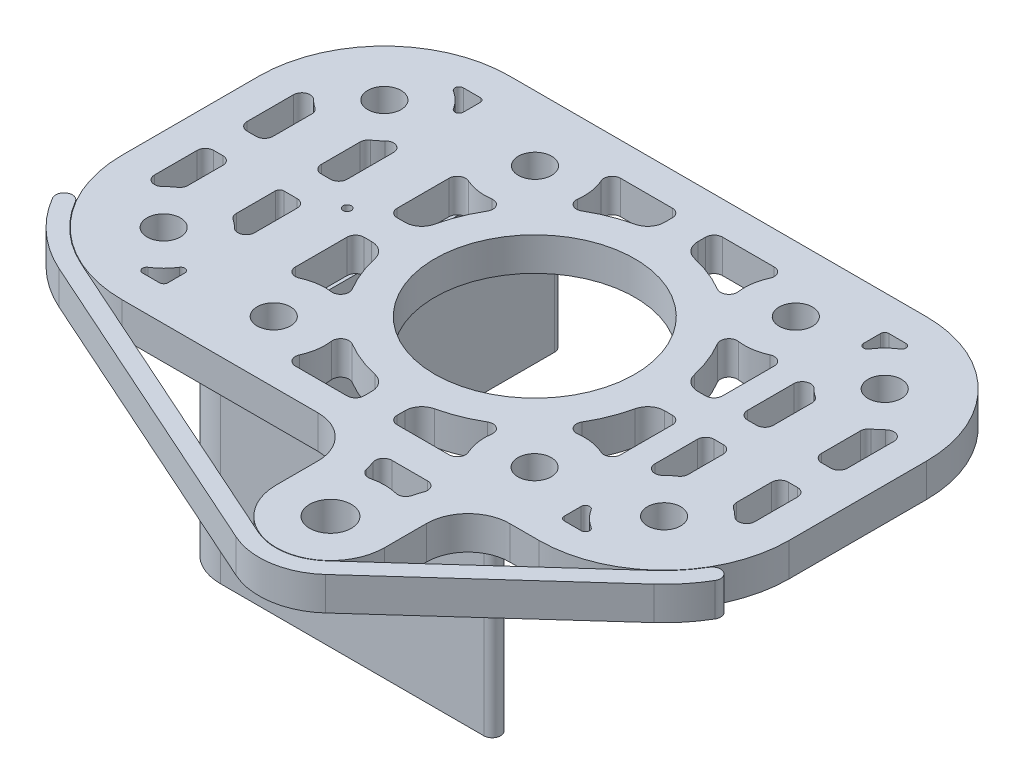
SolidWorks part; units mm, degrees
ref_plane "Front Plane" through (0, 0, 0) normal (0, 0, 1) x (1, 0, 0)
ref_plane "Top Plane" through (0, 0, 0) normal (0, 1, 0) x (1, 0, 0)
ref_plane "Right Plane" through (0, 0, 0) normal (1, 0, 0) x (0, 0, -1)
sketch "Sketch1" plane through (0, 0, 0) normal (0, 1, 0) x (1, 0, 0)
  line L1 (-21.5, 13.9196) -> (-21.5, 17.5) construction
  line L2 (-17.5, -21.5) -> (17.5, -21.5) construction
  line L3 (19.5, -3) -> (19.5, -9.2063)
  line L4 (19.5, 9.2063) -> (19.5, 3)
  line L5 (21.5, 21.5) -> (-21.5, -21.5) construction
  line L7 (-17.5, 21.5) -> (17.5, 21.5) construction
  line L8 (-11.4637, 10) -> (-11.4637, -10) construction
  line L9 (-11.4637, 10) -> (-11.4637, -10) construction
  line L10 (0, 0) -> (0, 15.6621) construction
  line L11 (0, 15.6621) -> (-15.6378, 15.6621) construction
  line L13 (-26.5, -23) -> (-3, -23)
  line L14 (0, -21.5) -> (0, 38.5) construction
  line L15 (-26.5, 23.4637) -> (23.5, 23.4637)
  line L16 (38.5, -8) -> (38.5, 8.4637)
  line L17 (21.5, -17.5) -> (21.5, 17.5) construction
  line L18 (-41.5, 8.4637) -> (-41.5, -8)
  line L19 (-31.5, 7.4637) -> (-31.5, -7) construction
  line L21 (-21.5, -21.5) -> (21.5, 21.5) construction
  line L22 (18.5, 2) -> (17.5499, 2)
  line L23 (-34.4, 7.6508) -> (-34.4, 3)
  line L27 (-28.6, 7.6508) -> (-28.6, 3)
  line L28 (-25.5, 8.5647) -> (-25.5, 3)
  line L29 (-37.5, -8.101) -> (-37.5, -3)
  line L30 (18.5, -2) -> (17.5499, -2)
  line L31 (-3, -19.5) -> (-9.2063, -19.5)
  line L32 (9.2063, -19.5) -> (3, -19.5)
  line L33 (12.6, -23) -> (12.6, -43) construction
  line L34 (2, -18.5) -> (2, -17.5499)
  line L35 (-2, -18.5) -> (-2, -17.5499)
  line L36 (-19.5, 3) -> (-19.5, 9.2063)
  line L37 (-19.5, -9.2063) -> (-19.5, -3)
  line L38 (-18.5, -2) -> (-17.5499, -2)
  line L39 (-9.2063, 19.5) -> (-3, 19.5)
  line L40 (-25.5, 16.9278) -> (-25.5, 18.9637)
  line L41 (2, 18.5) -> (2, 17.5499)
  line L42 (-2, 18.5) -> (-2, 17.5499)
  line L43 (3, 19.5) -> (9.2063, 19.5)
  line L44 (0, 23.4637) -> (0, 16) construction
  line L45 (-18.5, 2) -> (-17.5499, 2)
  line L47 (18.5, 38.5) -> (38.5, 38.5) construction
  line L48 (-26.5, -2) -> (-28.1, -2)
  line L51 (-25.5, -16.4641) -> (-25.5, -18.5)
  line L52 (-20.3267, -20.3302) -> (-20.3284, -20.3284)
  line L53 (-28.0359, -19) -> (-26, -19)
  line L54 (0, -23.4637) -> (0, -16) construction
  line L55 (-21.5, 623) -> (-21.5, -43) construction
  line L56 (18.5, -23) -> (18.5, 603) construction
  line L57 (12.8901, -37.861) -> (33.5871, -19.1693)
  line L58 (-19.5, -23) -> (-15.6, -23) construction
  line L59 (5.8213, -38.9772) -> (-32.6549, -21.7339)
  line L60 (12.6, -43) -> (12.6, -63) construction
  line L61 (-18.9133, -18.9151) -> (-18.9142, -18.9142)
  line L62 (-26.5, 2) -> (-27.6, 2)
  line L63 (-21.5, 38.5) -> (-41.5, 38.5) construction
  line L65 (-28.0359, 19.4637) -> (-26, 19.4637)
  line L66 (23, -19.4637) -> (25.0359, -19.4637)
  line L67 (-34.4, -3) -> (-34.4, -7.1871)
  line L68 (-37.5, 3) -> (-37.5, 8.5647)
  line L69 (-35.4, 2) -> (-36.5, 2)
  line L70 (-35.4, -2) -> (-36.5, -2)
  line L71 (-28.6, -2.5) -> (-28.6, -7.1871)
  line L72 (-25.5, -3) -> (-25.5, -8.101)
  line L73 (22.5, -8.101) -> (22.5, -3)
  line L74 (28.5, 7.4637) -> (28.5, -7) construction
  line L75 (-26.5, -3) -> (-18.5, 3) construction
  line L76 (-31.5, 27.4637) -> (28.5, 27.4637) construction
  line L77 (-26.5, 3) -> (-18.5, -3) construction
  line L78 (22.5, 16.9278) -> (22.5, 18.9637)
  line L79 (34.5, -8.101) -> (34.5, -3)
  line L80 (25.6, 7.6508) -> (25.6, 3)
  line L81 (31.4, 7.6508) -> (31.4, 3)
  line L82 (23, 19.4637) -> (25.0359, 19.4637)
  line L83 (22.5, -16.9278) -> (22.5, -18.9637)
  line L84 (17.5499, 2) -> (17.5499, -2) construction
  line L85 (22.5, 0) -> (25.6, 0) construction
  line L86 (23.5, -2) -> (24.6, -2)
  line L87 (23.5, 2) -> (24.6, 2)
  line L88 (-31.5, 23.4637) -> (28.5, 23.4637) construction
  line L89 (15, -33) -> (15, -28)
  line L90 (32.4, -2) -> (33.5, -2)
  line L91 (25.6, -3) -> (25.6, -7.1871)
  line L92 (28.5, 38.5) -> (28.5, 26.8752) construction
  line L93 (31.4, -3) -> (31.4, -7.1871)
  line L94 (32.4, 2) -> (33.5, 2)
  line L95 (22.5, 3) -> (22.5, 8.5647)
  line L96 (34.5, 3) -> (34.5, 8.5647)
  line L97 (2, -33) -> (2, -28)
  line L98 (20, -23) -> (23.5, -23)
  line L100 (5.0034, -40.8023) -> (-33.4728, -23.559)
  line L101 (10.6325, -23.5) -> (6.3675, -23.5)
  line L102 (14.2306, -39.3453) -> (34.9276, -20.6536)
  line L103 (9.2063, -23.5) -> (3, -23.5) construction
  arc A0 (23.5, -23) -> (38.5, -8) centre (23.5, -8) ccw
  arc A1 (38.5, 8.4637) -> (23.5, 23.4637) centre (23.5, 8.4637) ccw
  arc A2 (-26.5, 23.4637) -> (-41.5, 8.4637) centre (-26.5, 8.4637) ccw
  arc A3 (-17.5, 21.5) -> (-21.5, 17.5) centre (-17.5, 17.5) ccw construction
  arc A4 (-21.5, -17.5) -> (-17.5, -21.5) centre (-17.5, -17.5) ccw construction
  arc A5 (-41.5, -8) -> (-26.5, -23) centre (-26.5, -8) ccw
  circle A7 centre (-31.5, 13.4637) radius 2
  circle A9 centre (28.5, 13.4637) radius 2
  circle A10 centre (0, 0) radius 12
  circle A11 centre (-15.6378, 15.6621) radius 2
  circle A12 centre (15.6621, 15.6378) radius 2
  circle A13 centre (0, 0) radius 3.7
  arc A14 (21.5, -17.5) -> (17.5, -21.5) centre (17.5, -17.5) cw construction
  arc A15 (17.5, 21.5) -> (21.5, 17.5) centre (17.5, 17.5) cw construction
  circle A20 centre (15.6378, -15.6621) radius 2
  circle A21 centre (-15.6621, -15.6378) radius 2
  circle A22 centre (28.5, -13) radius 2
  circle A23 centre (-31.5, -13) radius 2
  arc A24 (-28.1571, 8.4812) -> (-27.2143, 9.2646) centre (-31.5, 13.4637) ccw
  arc A25 (-34.8429, -8.0175) -> (-35.7857, -8.8009) centre (-31.5, -13) ccw
  arc A26 (31.8429, 8.4812) -> (32.7857, 9.2646) centre (28.5, 13.4637) ccw
  arc A27 (25.1571, -8.0175) -> (24.2143, -8.8009) centre (28.5, -13) ccw
  arc A28 (-26.4231, 16.6614) -> (-28.3024, 18.5406) centre (-31.5, 13.4637) ccw
  arc A29 (-27.2143, -8.8009) -> (-28.1571, -8.0175) centre (-31.5, -13) ccw
  arc A30 (-35.7857, 9.2646) -> (-34.8429, 8.4812) centre (-31.5, 13.4637) ccw
  arc A31 (-28.3024, -18.0769) -> (-26.4231, -16.1976) centre (-31.5, -13) ccw
  arc A32 (13.7831, -8.1256) -> (15.5999, -3.5556) centre (0, 0) ccw
  arc A33 (13.7831, -8.1256) -> (14.7756, -9.6248) centre (14.6446, -8.6335) ccw
  arc A34 (18.0864, -10.1167) -> (14.7756, -9.6248) centre (15.5724, -15.6501) ccw
  arc A35 (17.5499, -2) -> (15.5999, -3.5556) centre (17.5499, -4) ccw
  arc A36 (18.0864, -10.1167) -> (19.5, -9.2063) centre (18.5, -9.2063) ccw
  arc A37 (19.5, -3) -> (18.5, -2) centre (18.5, -3) ccw
  arc A38 (18.0864, 10.1167) -> (14.7756, 9.6248) centre (15.5724, 15.6501) cw
  arc A39 (17.5499, 2) -> (15.5999, 3.5556) centre (17.5499, 4) cw
  arc A40 (13.7831, 8.1256) -> (14.7756, 9.6248) centre (14.6446, 8.6335) cw
  arc A41 (13.7831, 8.1256) -> (15.5999, 3.5556) centre (0, 0) cw
  arc A42 (18.5, 2) -> (19.5, 3) centre (18.5, 3) ccw
  arc A43 (18.0864, 10.1167) -> (19.5, 9.2063) centre (18.5, 9.2063) cw
  arc A44 (-8.1256, -13.7831) -> (-3.5556, -15.5999) centre (0, 0) ccw
  arc A45 (-10.1167, 18.0864) -> (-9.6248, 14.7756) centre (-15.6501, 15.5724) cw
  arc A46 (8.1256, 13.7831) -> (3.5556, 15.5999) centre (0, 0) ccw
  arc A47 (-8.1256, -13.7831) -> (-9.6248, -14.7756) centre (-8.6335, -14.6446) ccw
  arc A48 (8.1256, 13.7831) -> (9.6248, 14.7756) centre (8.6335, 14.6446) ccw
  arc A49 (10.1167, 18.0864) -> (9.6248, 14.7756) centre (15.6501, 15.5724) ccw
  arc A50 (2, 17.5499) -> (3.5556, 15.5999) centre (4, 17.5499) ccw
  arc A51 (-2, 17.5499) -> (-3.5556, 15.5999) centre (-4, 17.5499) cw
  arc A52 (-10.1167, -18.0864) -> (-9.6248, -14.7756) centre (-15.6501, -15.5724) ccw
  arc A53 (-8.1256, 13.7831) -> (-9.6248, 14.7756) centre (-8.6335, 14.6446) cw
  arc A54 (-2, -17.5499) -> (-3.5556, -15.5999) centre (-4, -17.5499) ccw
  arc A55 (-8.1256, 13.7831) -> (-3.5556, 15.5999) centre (0, 0) cw
  arc A56 (-10.1167, -18.0864) -> (-9.2063, -19.5) centre (-9.2063, -18.5) ccw
  arc A57 (-3, -19.5) -> (-2, -18.5) centre (-3, -18.5) ccw
  arc A58 (10.1167, -18.0864) -> (9.6248, -14.7756) centre (15.6501, -15.5724) cw
  arc A59 (2, -17.5499) -> (3.5556, -15.5999) centre (4, -17.5499) cw
  arc A60 (8.1256, -13.7831) -> (9.6248, -14.7756) centre (8.6335, -14.6446) cw
  arc A61 (8.1256, -13.7831) -> (3.5556, -15.5999) centre (0, 0) cw
  arc A62 (2, -18.5) -> (3, -19.5) centre (3, -18.5) ccw
  arc A63 (10.1167, -18.0864) -> (9.2063, -19.5) centre (9.2063, -18.5) cw
  arc A64 (-13.7831, 8.1256) -> (-15.5999, 3.5556) centre (0, 0) ccw
  arc A65 (-13.7831, 8.1256) -> (-14.7756, 9.6248) centre (-14.6446, 8.6335) ccw
  arc A66 (-18.0864, 10.1167) -> (-14.7756, 9.6248) centre (-15.5724, 15.6501) ccw
  arc A67 (-17.5499, 2) -> (-15.5999, 3.5556) centre (-17.5499, 4) ccw
  arc A68 (-18.0864, 10.1167) -> (-19.5, 9.2063) centre (-18.5, 9.2063) ccw
  arc A69 (-19.5, 3) -> (-18.5, 2) centre (-18.5, 3) ccw
  arc A70 (-18.0864, -10.1167) -> (-14.7756, -9.6248) centre (-15.5724, -15.6501) cw
  arc A71 (-17.5499, -2) -> (-15.5999, -3.5556) centre (-17.5499, -4) cw
  arc A72 (-13.7831, -8.1256) -> (-14.7756, -9.6248) centre (-14.6446, -8.6335) cw
  arc A73 (10.1167, 18.0864) -> (9.2063, 19.5) centre (9.2063, 18.5) ccw
  arc A74 (-13.7831, -8.1256) -> (-15.5999, -3.5556) centre (0, 0) cw
  arc A75 (-18.5, -2) -> (-19.5, -3) centre (-18.5, -3) ccw
  arc A76 (3, 19.5) -> (2, 18.5) centre (3, 18.5) ccw
  arc A77 (-18.0864, -10.1167) -> (-19.5, -9.2063) centre (-18.5, -9.2063) cw
  arc A78 (-2, 18.5) -> (-3, 19.5) centre (-3, 18.5) ccw
  arc A79 (-28.6, -7.1871) -> (-28.1571, -8.0175) centre (-27.6, -7.1871) ccw
  arc A80 (-10.1167, 18.0864) -> (-9.2063, 19.5) centre (-9.2063, 18.5) cw
  arc A81 (-25.5, -8.101) -> (-27.2143, -8.8009) centre (-26.5, -8.101) cw
  arc A82 (-37.5, -8.101) -> (-35.7857, -8.8009) centre (-36.5, -8.101) ccw
  arc A83 (-34.4, -7.1871) -> (-34.8429, -8.0175) centre (-35.4, -7.1871) cw
  arc A84 (-34.4, 7.6508) -> (-34.8429, 8.4812) centre (-35.4, 7.6508) ccw
  arc A85 (-28.6, 7.6508) -> (-28.1571, 8.4812) centre (-27.6, 7.6508) cw
  arc A86 (-25.5, 8.5647) -> (-27.2143, 9.2646) centre (-26.5, 8.5647) ccw
  arc A87 (-37.5, 8.5647) -> (-35.7857, 9.2646) centre (-36.5, 8.5647) cw
  arc A88 (24.6, -2) -> (25.6, -3) centre (24.6, -3) cw
  arc A89 (23.5, -2) -> (22.5, -3) centre (23.5, -3) ccw
  arc A90 (32.7857, -8.8009) -> (31.8429, -8.0175) centre (28.5, -13) ccw
  arc A91 (25.3024, 18.5406) -> (23.4231, 16.6614) centre (28.5, 13.4637) ccw
  arc A92 (25.6, -7.1871) -> (25.1571, -8.0175) centre (24.6, -7.1871) cw
  arc A93 (22.5, -8.101) -> (24.2143, -8.8009) centre (23.5, -8.101) ccw
  arc A94 (32.4, -2) -> (31.4, -3) centre (32.4, -3) ccw
  arc A95 (34.5, -3) -> (33.5, -2) centre (33.5, -3) ccw
  arc A96 (31.4, -7.1871) -> (31.8429, -8.0175) centre (32.4, -7.1871) ccw
  arc A97 (34.5, -8.101) -> (32.7857, -8.8009) centre (33.5, -8.101) cw
  arc A98 (34.5, 3) -> (33.5, 2) centre (33.5, 3) cw
  arc A99 (31.4, 7.6508) -> (31.8429, 8.4812) centre (32.4, 7.6508) cw
  arc A100 (34.5, 8.5647) -> (32.7857, 9.2646) centre (33.5, 8.5647) ccw
  arc A101 (31.4, 3) -> (32.4, 2) centre (32.4, 3) ccw
  arc A102 (23.5, 2) -> (22.5, 3) centre (23.5, 3) cw
  arc A103 (24.6, 2) -> (25.6, 3) centre (24.6, 3) ccw
  arc A104 (25.6, 7.6508) -> (25.1571, 8.4812) centre (24.6, 7.6508) ccw
  arc A105 (22.5, 8.5647) -> (24.2143, 9.2646) centre (23.5, 8.5647) cw
  arc A106 (24.2143, 9.2646) -> (25.1571, 8.4812) centre (28.5, 13.4637) ccw
  arc A107 (25.3024, -18.5406) -> (23.4231, -16.6614) centre (28.5, -13.4637) cw
  arc A108 (-27.6, 2) -> (-28.6, 3) centre (-27.6, 3) cw
  arc A109 (-34.4, -3) -> (-35.4, -2) centre (-35.4, -3) ccw
  arc A110 (-34.4, 3) -> (-35.4, 2) centre (-35.4, 3) cw
  arc A111 (-36.5, 2) -> (-37.5, 3) centre (-36.5, 3) cw
  arc A112 (-26.5, 2) -> (-25.5, 3) centre (-26.5, 3) ccw
  arc A113 (-36.5, -2) -> (-37.5, -3) centre (-36.5, -3) ccw
  arc A114 (-26.5, -2) -> (-25.5, -3) centre (-26.5, -3) cw
  arc A115 (-27.6, -2) -> (-28.6, -3) centre (-27.6, -3) ccw
  arc A116 (-28.3024, 18.5406) -> (-28.0359, 19.4637) centre (-28.0359, 18.9637) cw
  arc A117 (-25.5, 18.9637) -> (-26, 19.4637) centre (-26, 18.9637) ccw
  arc A118 (-25.5, 16.9278) -> (-26.4231, 16.6614) centre (-26, 16.9278) cw
  arc A119 (-28.3024, -18.0769) -> (-28.0359, -19) centre (-28.0359, -18.5) ccw
  arc A120 (-25.5, -18.5) -> (-26, -19) centre (-26, -18.5) cw
  arc A121 (-25.5, -16.4641) -> (-26.4231, -16.1976) centre (-26, -16.4641) ccw
  arc A122 (-28.1, -2) -> (-28.6, -2.5) centre (-28.1, -2.5) ccw
  arc A123 (22.5, 18.9637) -> (23, 19.4637) centre (23, 18.9637) cw
  arc A124 (22.5, 16.9278) -> (23.4231, 16.6614) centre (23, 16.9278) ccw
  arc A125 (25.0359, 19.4637) -> (25.3024, 18.5406) centre (25.0359, 18.9637) cw
  arc A126 (-28.1, -2) -> (-28.6, -2.5) centre (-28.1, -2.5) ccw
  arc A127 (23, -19.4637) -> (22.5, -18.9637) centre (23, -18.9637) cw
  arc A128 (25.3024, -18.5406) -> (25.0359, -19.4637) centre (25.0359, -18.9637) cw
  arc A129 (-28.1, -2) -> (-28.6, -2.5) centre (-28.1, -2.5) ccw
  arc A130 (23.4231, -16.6614) -> (22.5, -16.9278) centre (23, -16.9278) ccw
  arc A131 (-28.1, -2) -> (-28.6, -2.5) centre (-28.1, -2.5) ccw
  circle A132 centre (-22.5, 0) radius 0.5
  circle A133 centre (8.5, -33) radius 2.5 construction
  circle A134 centre (8.5, -33) radius 2.5
  arc A135 (2, -33) -> (15, -33) centre (8.5, -33) ccw
  arc A136 (10.0301, -26.6827) -> (6.9699, -26.6827) centre (8.5, -33) ccw
  arc A137 (-3, -23) -> (2, -28) centre (-3, -28) cw
  arc A138 (15, -28) -> (20, -23) centre (20, -28) cw
  arc A139 (11.239, -25.9397) -> (11.5693, -24.85) centre (20, -28) cw
  arc A140 (-3, -19) -> (3.2249, -21.5) centre (-3, -28) cw
  arc A141 (10.6325, -23.5) -> (11.5693, -24.85) centre (10.6325, -24.5) cw
  arc A142 (11, -28) -> (20, -19) centre (20, -28) cw construction
  arc A143 (5.4307, -24.85) -> (5.761, -25.9397) centre (-3, -28) cw
  arc A144 (-3, -19) -> (6, -28) centre (-3, -28) cw construction
  arc A145 (6.3675, -23.5) -> (5.4307, -24.85) centre (6.3675, -24.5) ccw
  arc A146 (6.9699, -26.6827) -> (5.761, -25.9397) centre (6.7344, -25.7108) cw
  arc A147 (10.0301, -26.6827) -> (11.239, -25.9397) centre (10.2656, -25.7108) ccw
  arc A148 (5.8213, -38.9772) -> (12.8901, -37.861) centre (8.5, -33) ccw
  arc A149 (-39.5, -15.583) -> (-32.6549, -21.7339) centre (-26.5, -8) ccw
  arc A150 (33.5871, -19.1693) -> (36.5, -15.583) centre (23.5, -8) ccw
  arc A151 (23.5, -23.05) -> (38.55, -8) centre (23.5, -8) ccw construction
  arc A152 (1.95, -33) -> (15.05, -33) centre (8.5, -33) ccw construction
  arc A153 (-41.55, -8) -> (-26.5, -23.05) centre (-26.5, -8) ccw construction
  arc A154 (-41.2276, -16.5908) -> (-33.4728, -23.559) centre (-26.5, -8) ccw
  arc A155 (5.0034, -40.8023) -> (14.2306, -39.3453) centre (8.5, -33) ccw
  arc A156 (34.9276, -20.6536) -> (38.2276, -16.5908) centre (23.5, -8) ccw
  arc A157 (-39.5, -15.583) -> (-41.2276, -16.5908) centre (-40.3638, -16.0869) ccw
  arc A158 (36.5, -15.583) -> (38.2276, -16.5908) centre (37.3638, -16.0869) cw
  point P0 (0.0699, 0.0699)
  point P5 (0, 0)
  point P51 (0, 0)
  point P98 (-25.5, -13)
  point P115 (-37.5, -13)
  point P119 (-11.2855, 11.3418)
  point P207 (0, 0)
  point P212 (-25.5, 13.4637)
  point P215 (-37.5, 13.4637)
  point P227 (0, 0)
  point P243 (37.5, 13.4637)
  point P244 (-21.5, -16.3317)
  point P253 (25.6, -2)
  point P261 (37.5, -13)
  point P275 (22.5, -13)
  point P278 (31.4, -2)
  point P287 (34.5, 2)
  point P297 (31.4, 2)
  point P306 (22.5, 13.4637)
  point P312 (-34.4, -2)
  point P315 (-34.4, 2)
  point P318 (-37.5, 2)
  point P325 (-25.5, -2)
  point P328 (-28.6, -2)
  point P335 (-25.5, 13.4637)
  point P342 (-25.5, -13)
  point P348 (22.5, 19.4637)
  point P351 (22.5, 13.4637)
  point P354 (28.5, 19.4637)
  point P360 (22.5, -19.4637)
  point P363 (28.5, -19.4637)
  point P367 (22.5, -13.4637)
  point P396 (4.7942, -23.5)
  point P407 (5.9468, -27.0225)
  dimension "D3" = 4
  dimension "D4" = 1
  dimension "D5" = 0.5
  dimension "D9" = 15
  dimension "D12" = 5
  dimension "D7" = 0.5
  dimension "D11" = 1
  dimension "D2" = 1
  dimension "D6" = 0.5
  dimension "D8" = 0.5
  dimension "D10" = 4
extrude "Boss-Extrude1" add sketch "Sketch1" along normal blind 4
sketch "Sketch2" plane through (0, 0, 0) normal (0, 1, 0) x (1, 0, 0)
  line L0 (18.5, -23) -> (18.5, 603) construction
  line L1 (18.5, -23) -> (18.5, 603) construction
  line L2 (-21.1, 623) -> (-21.1, -43)
  line L3 (-21.1, 21.4637) -> (-21.1, -16.6)
  line L4 (-26.5, 23.4637) -> (23.5, 23.4637) construction
  line L5 (-26.5, -22.6) -> (-3, -22.6)
  line L6 (-15.1, -22.6) -> (16.4993, -22.6)
  line L7 (-26.5, 23.4637) -> (23.5, 23.4637) construction
  line L8 (-19.1, 21.4637) -> (-19.1, -16.6)
  line L9 (-15.1, -20.6) -> (16.4993, -20.6)
  line L10 (-31.5, 8.4637) -> (-31.5, 5.5637) construction
  line L12 (-31.5, -8) -> (-31.5, -5.1) construction
  line L13 (-31.5, -5.1) -> (-31.5, 5.5637) construction
  line L14 (-28.6, -5.1) -> (-28.6, 5.5637) construction
  line L15 (-34.4, -5.1) -> (-34.4, 5.5637) construction
  line L16 (28.5, 5.5637) -> (28.5, -5.1) construction
  line L17 (28.5, 7.4637) -> (28.5, -7) construction
  line L18 (25.6, 5.5637) -> (25.6, -5.1) construction
  line L19 (31.4, 5.5637) -> (31.4, -5.1) construction
  arc A0 (-15.1, -22.6) -> (-21.1, -16.6) centre (-15.1, -16.6) cw
  arc A1 (-15.1, -20.6) -> (-19.1, -16.6) centre (-15.1, -16.6) cw
  arc A2 (-21.1, 21.4637) -> (-19.1, 21.4637) centre (-20.1, 21.4637) cw
  arc A3 (16.4993, -22.6) -> (16.4993, -20.6) centre (16.4993, -21.6) ccw
  circle A4 centre (-31.5, 13.4637) radius 5 construction
  circle A7 centre (-31.5, -13) radius 5 construction
  arc A8 (-28.6, -5.1) -> (-34.4, -5.1) centre (-31.5, -5.1) cw construction
  arc A9 (-28.6, 5.5637) -> (-34.4, 5.5637) centre (-31.5, 5.5637) ccw construction
  arc A10 (25.6, 5.5637) -> (31.4, 5.5637) centre (28.5, 5.5637) cw construction
  arc A11 (25.6, -5.1) -> (31.4, -5.1) centre (28.5, -5.1) ccw construction
  dimension "D3" = 6
  dimension "D5" = 2.9
  dimension "D6" = 2.9
  dimension "D1" = 0.4
  dimension "D2" = 0.4
  dimension "D4" = 2
extrude "Boss-Extrude2" add sketch "Sketch2" against normal blind 20
sketch "Sketch3" plane through (0, 0, 0) normal (0, 1, 0) x (1, 0, 0)
  line L0 (31.4, 5.5637) -> (31.4, -5.1) construction
  line L1 (25.6, 5.5637) -> (25.6, -5.1) construction
  line L2 (-28.6, -5.1) -> (-28.6, 5.5637) construction
  line L3 (-34.4, -5.1) -> (-34.4, 5.5637) construction
  line L4 (31.4, 5.5637) -> (31.4, -5.1)
  line L5 (25.6, 5.5637) -> (25.6, -5.1)
  line L6 (-28.6, -5.1) -> (-28.6, 5.5637)
  line L7 (-34.4, -5.1) -> (-34.4, 5.5637)
  line L16 (-32.4, -5.1) -> (-32.4, 5.5637)
  line L17 (-30.6, -5.1) -> (-30.6, 5.5637)
  line L18 (27.6, 5.5637) -> (27.6, -5.1)
  line L19 (29.4, 5.5637) -> (29.4, -5.1)
  arc A0 (31.4, 5.5637) -> (25.6, 5.5637) centre (28.5, 5.5637) ccw construction
  arc A1 (25.6, -5.1) -> (31.4, -5.1) centre (28.5, -5.1) ccw construction
  arc A2 (-34.4, -5.1) -> (-28.6, -5.1) centre (-31.5, -5.1) ccw construction
  arc A3 (-28.6, 5.5637) -> (-34.4, 5.5637) centre (-31.5, 5.5637) ccw construction
  arc A4 (31.4, 5.5637) -> (25.6, 5.5637) centre (28.5, 5.5637) ccw
  arc A5 (25.6, -5.1) -> (31.4, -5.1) centre (28.5, -5.1) ccw
  arc A6 (-34.4, -5.1) -> (-28.6, -5.1) centre (-31.5, -5.1) ccw
  arc A7 (-28.6, 5.5637) -> (-34.4, 5.5637) centre (-31.5, 5.5637) ccw
  arc A16 (-30.6, 5.5637) -> (-32.4, 5.5637) centre (-31.5, 5.5637) ccw
  arc A17 (-32.4, -5.1) -> (-30.6, -5.1) centre (-31.5, -5.1) ccw
  arc A18 (29.4, 5.5637) -> (27.6, 5.5637) centre (28.5, 5.5637) ccw
  arc A19 (27.6, -5.1) -> (29.4, -5.1) centre (28.5, -5.1) ccw
  dimension "D1" = 2
  dimension "D2" = 2
extrude "Boss-Extrude3" add sketch "Sketch3" against normal blind 3
ref_plane "Plane1" through (0, 51.5, 0) normal (0, 1, 0) x (1, 0, 0)
sketch "Sketch5" plane through (0, 51.5, 0) normal (0, 1, 0) x (1, 0, 0)
  line L0 (-21, 17) -> (-21, -17) construction
  line L1 (-21, -17) -> (-17, -21) construction
  line L2 (-17, -21) -> (17, -21) construction
  line L3 (17, -21) -> (21, -17) construction
  line L4 (21, -17) -> (21, 17) construction
  line L5 (21, 17) -> (17, 21) construction
  line L6 (17, 21) -> (-17, 21) construction
  line L7 (-17, 21) -> (-21, 17) construction
  line L8 (-21.5, 16.5) -> (-21.5, -16.5)
  line L9 (-21.5, 17.2071) -> (-21.5, -17.2071) construction
  line L10 (-16.5, -21.5) -> (16.5, -21.5)
  line L11 (-17.2071, -21.5) -> (17.2071, -21.5) construction
  line L12 (21.5, -16.5) -> (21.5, 16.5)
  line L13 (21.5, -17.2071) -> (21.5, 17.2071) construction
  line L14 (16.5, 21.5) -> (-16.5, 21.5)
  line L15 (17.2071, 21.5) -> (-17.2071, 21.5) construction
  line L16 (-17.2071, 21.5) -> (-21.5, 17.2071) construction
  line L17 (-21.5, -17.2071) -> (-17.2071, -21.5) construction
  line L18 (17.2071, -21.5) -> (21.5, -17.2071) construction
  line L19 (21.5, 17.2071) -> (17.2071, 21.5) construction
  circle A0 centre (0, 0) radius 12 construction
  arc A1 (-21.5, -16.5) -> (-16.5, -21.5) centre (-16.5, -16.5) ccw
  arc A2 (16.5, -21.5) -> (21.5, -16.5) centre (16.5, -16.5) ccw
  arc A3 (21.5, 16.5) -> (16.5, 21.5) centre (16.5, 16.5) ccw
  arc A4 (-16.5, 21.5) -> (-21.5, 16.5) centre (-16.5, 16.5) ccw
  dimension "D2" = 5
  dimension "D1" = 0.5
sketch "Sketch6" plane through (0, 4, 0) normal (0, 1, 0) x (1, 0, 0)
  line L4 (-41.5, 8.4637) -> (-41.5, -8)
  line L5 (-26.5, -23) -> (-3, -23)
  line L6 (38.5, -8) -> (38.5, 8.4637)
  line L7 (23.5, 23.4637) -> (-26.5, 23.4637)
  line L8 (-41.5, 8.4637) -> (-41.5, -8)
  line L9 (-26.5, -23) -> (-3, -23)
  line L10 (38.5, -8) -> (38.5, 8.4637)
  line L11 (23.5, 23.4637) -> (-26.5, 23.4637)
  line L15 (15, -33) -> (15, -28)
  line L16 (15, -33) -> (15, -28)
  line L17 (20, -23) -> (23.5, -23)
  line L18 (20, -23) -> (23.5, -23)
  line L19 (2, -28) -> (2, -33)
  line L20 (2, -28) -> (2, -33)
  arc A4 (-41.5, -8) -> (-26.5, -23) centre (-26.5, -8) ccw
  arc A5 (23.5, -23) -> (38.5, -8) centre (23.5, -8) ccw
  arc A6 (38.5, 8.4637) -> (23.5, 23.4637) centre (23.5, 8.4637) ccw
  arc A7 (-26.5, 23.4637) -> (-41.5, 8.4637) centre (-26.5, 8.4637) ccw
  arc A8 (-41.5, -8) -> (-26.5, -23) centre (-26.5, -8) ccw
  arc A9 (23.5, -23) -> (38.5, -8) centre (23.5, -8) ccw
  arc A10 (38.5, 8.4637) -> (23.5, 23.4637) centre (23.5, 8.4637) ccw
  arc A11 (-26.5, 23.4637) -> (-41.5, 8.4637) centre (-26.5, 8.4637) ccw
  arc A15 (20, -23) -> (15, -28) centre (20, -28) ccw
  arc A16 (20, -23) -> (15, -28) centre (20, -28) ccw
  arc A17 (2, -28) -> (-3, -23) centre (-3, -28) ccw
  arc A18 (2, -28) -> (-3, -23) centre (-3, -28) ccw
  arc A19 (2, -33) -> (15, -33) centre (8.5, -33) ccw
  arc A20 (2, -33) -> (15, -33) centre (8.5, -33) ccw
  dimension "D1" = 0
